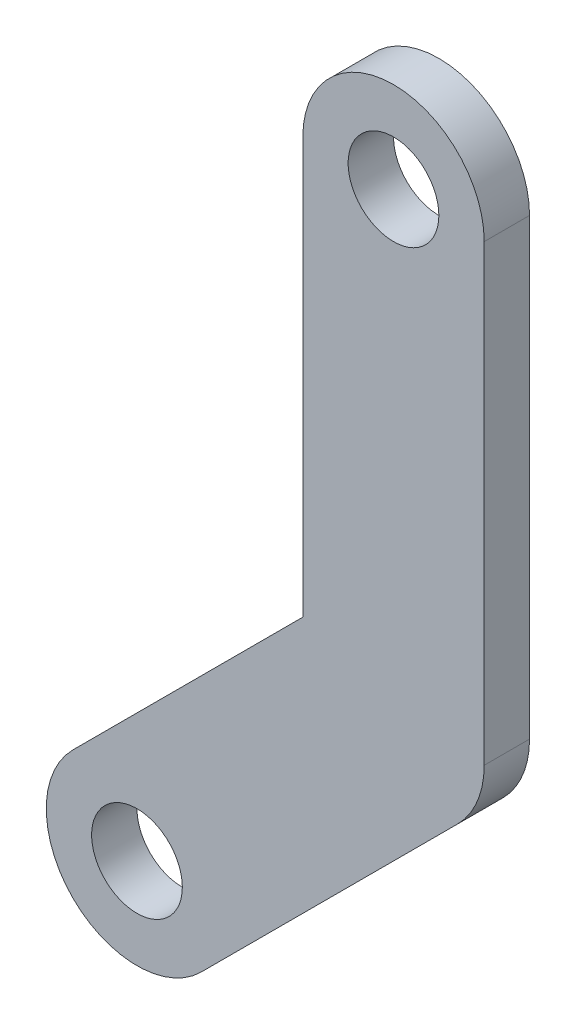
SolidWorks part; units mm, degrees
ref_plane "Plan de face" through (0, 0, 0) normal (0, 0, 1) x (1, 0, 0)
ref_plane "Plan de dessus" through (0, 0, 0) normal (0, 1, 0) x (1, 0, 0)
ref_plane "Plan de droite" through (0, 0, 0) normal (1, 0, 0) x (0, 0, -1)
sketch "Esquisse1" plane through (0, 0, 0) normal (0, 0, 1) x (1, 0, 0)
  line L0 (0, 0) -> (56.5685, 56.5685) construction
  line L1 (0, 0) -> (56.5685, 56.5685) construction
  line L2 (-14.1421, 14.1421) -> (42.4264, 70.7107)
  line L3 (14.1421, -14.1421) -> (70.7107, 42.4264)
  line L4 (56.5685, 56.5685) -> (56.5685, 156.5685) construction
  line L5 (36.5685, 56.5685) -> (36.5685, 156.5685)
  line L6 (76.5685, 56.5685) -> (76.5685, 156.5685)
  line L7 (0, 0) -> (0, 211.9554) construction
  arc A0 (-14.1421, 14.1421) -> (14.1421, -14.1421) centre (0, 0) ccw
  arc A1 (70.7107, 42.4264) -> (42.4264, 70.7107) centre (56.5685, 56.5685) ccw
  arc A2 (36.5685, 56.5685) -> (76.5685, 56.5685) centre (56.5685, 56.5685) ccw
  arc A3 (76.5685, 156.5685) -> (36.5685, 156.5685) centre (56.5685, 156.5685) ccw
  circle A4 centre (0, 0) radius 10
  circle A5 centre (56.5685, 156.5685) radius 10
  point P3 (28.2843, 28.2843)
  point P10 (56.5685, 106.5685)
  dimension "D1" = 80
  dimension "D3" = 20
  dimension "D4" = 20
  dimension "D6" = 20
  dimension "D7" = 20
  dimension "D2" = 100
  dimension "D5" = 45
extrude "Boss.-Extru.1" add sketch "Esquisse1" along normal blind 10 contours L6 A3 L5 L2 A1 A5 | L5 A2 A1 L2 | A2 L5 L2 A0 L3 A4
